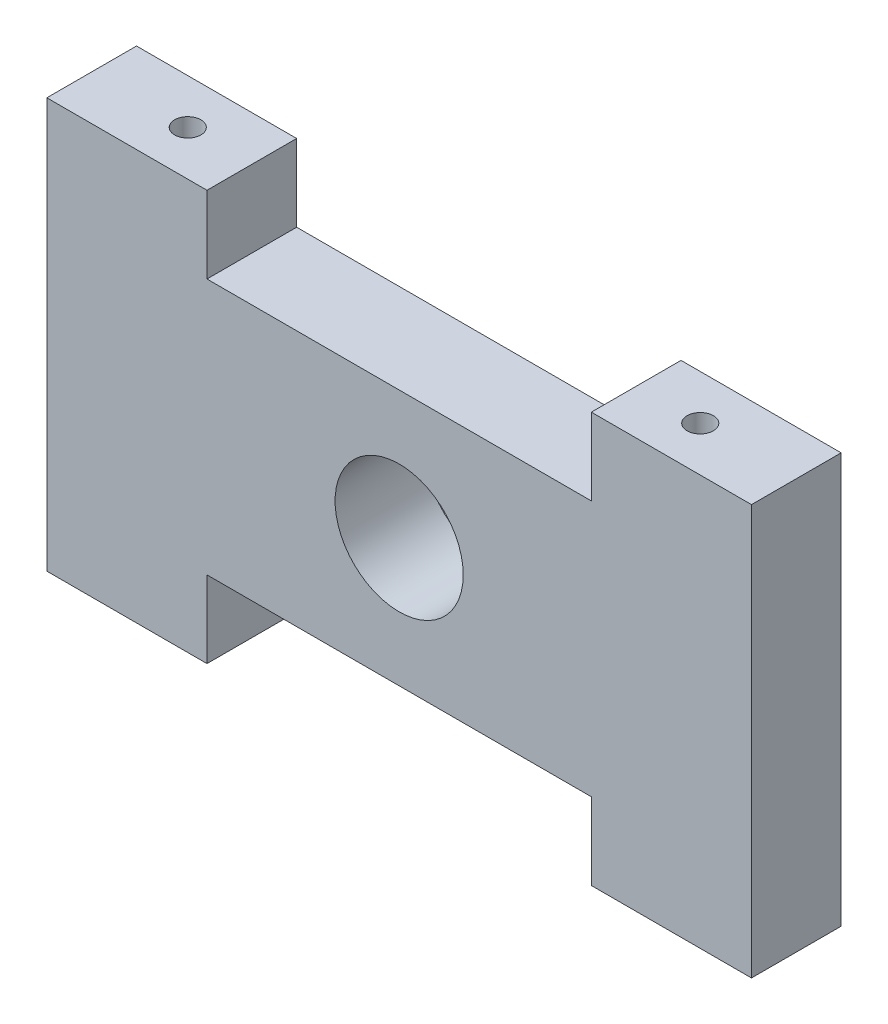
SolidWorks part; units mm, degrees
material "Thornel Mat VMA"
ref_plane "Front Plane" through (0, 0, 0) normal (0, 0, 1) x (1, 0, 0)
ref_plane "Top Plane" through (0, 0, 0) normal (0, 1, 0) x (1, 0, 0)
ref_plane "Right Plane" through (0, 0, 0) normal (1, 0, 0) x (0, 0, -1)
sketch "Sketch1" plane through (0, 0, 0) normal (0, 0, 1) x (1, 0, 0)
  line L0 (-15, 10) -> (-15, 16)
  line L1 (-27.5, 16) -> (-15, 16)
  line L2 (-27.5, 16) -> (-27.5, -16)
  line L3 (-27.5, -16) -> (-15, -16)
  line L4 (27.5, 16) -> (27.5, -16)
  line L7 (-15, -10) -> (15, -10)
  line L9 (-15, 10) -> (15, 10)
  line L13 (15, 10) -> (15, 16)
  line L14 (15, -10) -> (15, -16)
  line L15 (-15, -10) -> (-15, -16)
  line L16 (15, 16) -> (27.5, 16)
  line L17 (15, -16) -> (27.5, -16)
  circle A0 centre (0, 0) radius 5
  point P0 (0, 0)
  point P6 (0, 0)
  dimension "D5" = 10
  dimension "D1" = 32
  dimension "D2" = 55
  dimension "D3" = 30
  dimension "D4" = 20
extrude "Boss-Extrude1" add sketch "Sketch1" along normal blind 7
hole_wizard "M2.5x0.45 Tapped Hole1" positions "Sketch4" profile "Sketch5" tap size "M2.5x0.45" standard "Ansi Metric" end condition through all
sketch "Sketch4" plane through (0, 16, 0) normal (0, 1, 0) x (-1, 0, 0)
  line L0 (-27.5, 0) -> (-15, 0) construction
  line L1 (15, 0) -> (27.5, 0) construction
  point P0 (20, 3.5)
  point P1 (-20, 3.5)
  dimension "D1" = 20
  dimension "D2" = 20
  dimension "D3" = 3.5
  dimension "D4" = 3.5
sketch "Sketch5" plane through (-20, 16, 3.5) normal (1, 0, 0) x (0, 0, 1)
  line L0 (0, 0) -> (0, 32)
  line L1 (0, 32) -> (1.025, 32)
  line L2 (1.025, 32) -> (1.025, 0)
  line L5 (1.025, 0) -> (0, 0)
  line L11 (0, -6.35) -> (0, 107.95) construction
  dimension "Thru Tap Drill Dia." = 2.05
  dimension "Thru Tap Drill Depth" = 32
cosmetic thread "Hole Thread1" parameters "D2"=2.5
cosmetic thread "Hole Thread2" parameters "D2"=2.5
